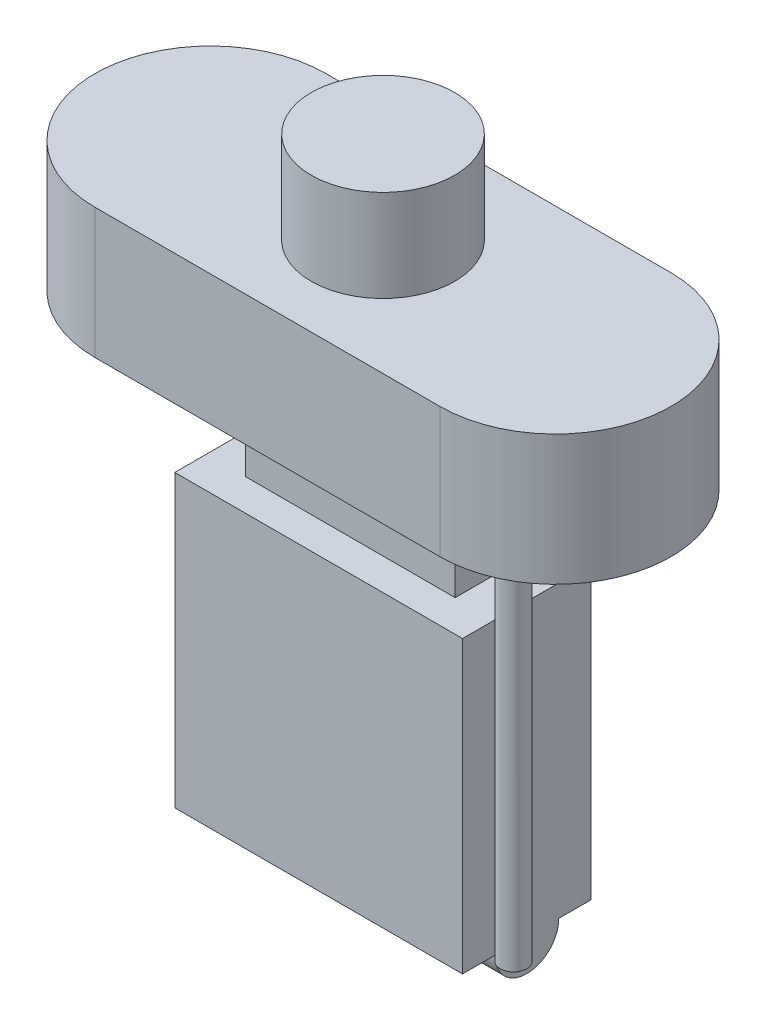
SolidWorks part; units mm, degrees
ref_plane "Plan de face" through (0, 0, 0) normal (0, 0, 1) x (1, 0, 0)
ref_plane "Plan de dessus" through (0, 0, 0) normal (0, 1, 0) x (1, 0, 0)
ref_plane "Plan de droite" through (0, 0, 0) normal (1, 0, 0) x (0, 0, -1)
sketch "Esquisse1" plane through (0, 0, 0) normal (0, 1, 0) x (1, 0, 0)
  line L0 (-23.8379, 0) -> (23.8379, 0) construction
  line L1 (-55, 0) -> (55, 0) construction
  line L2 (-23.8379, 15.9766) -> (23.8379, 15.9766)
  line L3 (-23.8379, -15.9766) -> (23.8379, -15.9766)
  arc A0 (-23.8379, 15.9766) -> (-23.8379, -15.9766) centre (-23.8379, 0) ccw
  arc A1 (23.8379, -15.9766) -> (23.8379, 15.9766) centre (23.8379, 0) ccw
  point P5 (0, 0)
  point P10 (39.8145, 0)
  point P12 (-39.8145, 0)
  dimension "D1" = 79.629
  dimension "D2" = 31.9532
extrude "Boss.-Extru.1" add sketch "Esquisse1" along normal mid plane 17.9832
sketch "Esquisse2" plane through (0, 8.9916, 0) normal (0, 1, 0) x (1, 0, 0)
  circle A0 centre (0, 0) radius 9.906
  dimension "D1" = 19.812
extrude "Boss.-Extru.2" add sketch "Esquisse2" along normal blind 12.7
sketch "Esquisse3" plane through (0, -8.9916, 0) normal (0, -1, 0) x (1, 0, 0)
  line L0 (-10.795, 0) -> (10.795, 0) construction
  line L1 (16.8758, 0) -> (-16.8758, 0) construction
  line L2 (-10.795, 9.525) -> (10.795, 9.525)
  line L3 (-10.795, -9.525) -> (10.795, -9.525)
  arc A0 (-10.795, 9.525) -> (-10.795, -9.525) centre (-10.795, 0) ccw
  arc A1 (10.795, -9.525) -> (10.795, 9.525) centre (10.795, 0) ccw
  point P5 (0, 0)
  point P10 (20.32, 0)
  point P11 (-20.32, 0)
  dimension "D1" = 40.64
  dimension "D2" = 19.05
extrude "Boss.-Extru.3" add sketch "Esquisse3" along normal blind 6.096
fillet "Congé1" radius 2.54 4 edges at (20.32, -8.9916, 0) (0, -8.9916, -9.525) (-20.32, -8.9916, 0) (0, -8.9916, 9.525)
sketch "Esquisse4" plane through (0, -15.0876, 0) normal (0, -1, 0) x (1, 0, 0)
  line L1 (-14.478, -4.5085) -> (14.478, -4.5085)
  line L2 (-14.478, -4.5085) -> (-14.478, 4.5085)
  line L3 (-14.478, 4.5085) -> (14.478, 4.5085)
  line L4 (14.478, -4.5085) -> (14.478, 4.5085)
  line L5 (-14.478, -4.5085) -> (14.478, 4.5085) construction
  line L6 (-14.478, 4.5085) -> (14.478, -4.5085) construction
  point P0 (0, 0)
  dimension "D1" = 9.017
  dimension "D2" = 28.956
extrude "Boss.-Extru.4" add sketch "Esquisse4" along normal blind 9.2202
sketch "Esquisse5" plane through (0, -24.3078, 0) normal (0, -1, 0) x (1, 0, 0)
  line L1 (-19.8755, -8.89) -> (19.8755, -8.89)
  line L2 (-19.8755, -8.89) -> (-19.8755, 8.89)
  line L3 (-19.8755, 8.89) -> (19.8755, 8.89)
  line L4 (19.8755, -8.89) -> (19.8755, 8.89)
  line L5 (-19.8755, -8.89) -> (19.8755, 8.89) construction
  line L6 (-19.8755, 8.89) -> (19.8755, -8.89) construction
  point P0 (0, 0)
  dimension "D1" = 17.78
  dimension "D2" = 39.751
extrude "Boss.-Extru.5" add sketch "Esquisse5" along normal blind 40.132
sketch "Esquisse6" plane through (19.8755, 0, 0) normal (1, 0, 0) x (0, 0, -1)
  line L0 (8.89, -64.4398) -> (-8.89, -64.4398) construction
  circle A0 centre (0, -64.4398) radius 4.4069
  dimension "D1" = 8.8138
extrude "Boss.-Extru.6" add sketch "Esquisse6" against normal up to surface (39.751 mm away) up to face at (-19.8755, -44.3738, 0)
sketch "Esquisse7" plane through (0, 0, -8.89) normal (0, 0, -1) x (-1, 0, 0)
  line L0 (0, 17.5743) -> (0, -17.5743) construction
  circle A0 centre (0, -45.4874) radius 2.921
  dimension "D1" = 5.842
extrude "Enlèv. mat.-Extru.1" cut sketch "Esquisse7" against normal blind 2.54
sketch "Esquisse8" plane through (0, -8.9916, 0) normal (0, -1, 0) x (1, 0, 0)
  circle A0 centre (26.5131, 8.4918) radius 1.825
  point P2 (26.5131, 8.4918)
  dimension "D1" = 3.65
extrude "Boss.-Extru.7" add sketch "Esquisse8" along normal blind 50.8
